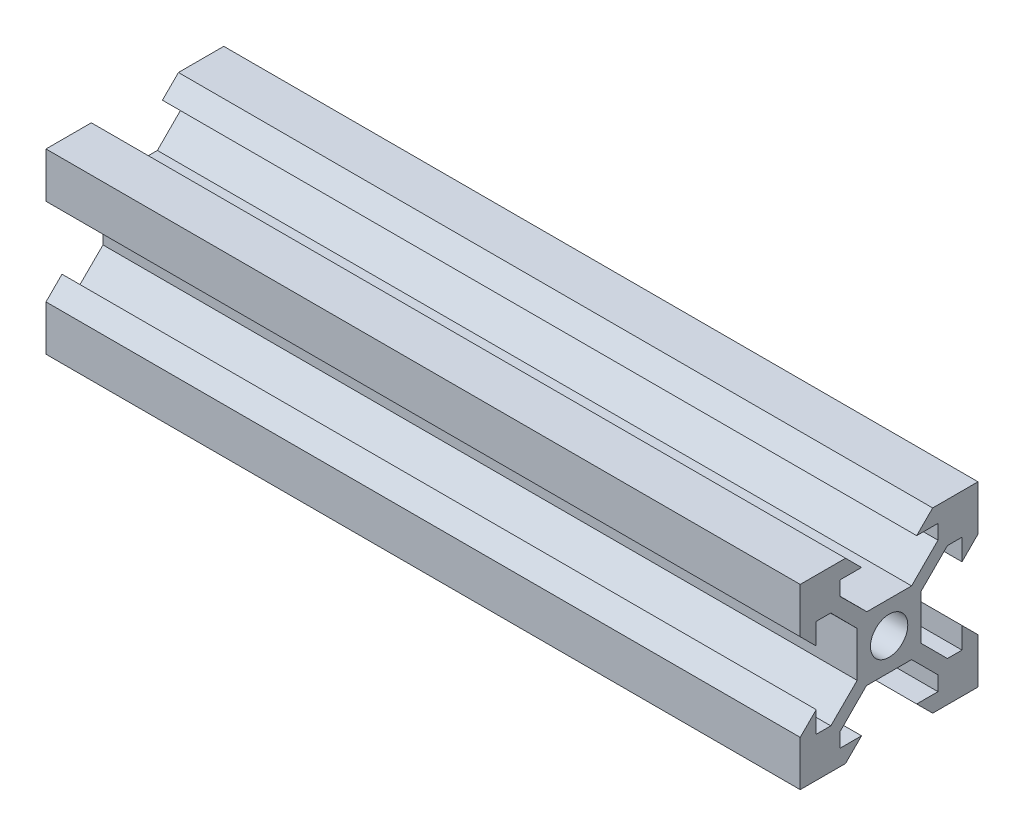
SolidWorks part; units mm, degrees
ref_plane "Front Plane" through (0, 0, 0) normal (0, 0, 1) x (1, 0, 0)
ref_plane "Top Plane" through (0, 0, 0) normal (0, 1, 0) x (1, 0, 0)
ref_plane "Right Plane" through (0, 0, 0) normal (1, 0, 0) x (0, 0, -1)
other "Graphic1"
sketch "Sketch1" plane through (0, 0, 0) normal (1, 0, 0) x (0, 0, -1)
  line L0 (-10, 20) -> (-4.9, 20)
  line L1 (-4.9, 20) -> (-3.1, 18.2)
  line L2 (-3.1, 18.2) -> (-5.4993, 18.2)
  line L3 (-5.4993, 18.2) -> (-5.4993, 16.56)
  line L4 (-5.4993, 16.56) -> (-2.5026, 13.59)
  line L5 (-2.5026, 13.59) -> (2.5293, 13.59)
  line L6 (2.5293, 13.59) -> (5.4993, 16.56)
  line L7 (5.4993, 16.56) -> (5.4993, 18.2)
  line L8 (5.4993, 18.2) -> (3.1, 18.2)
  line L9 (3.1, 18.2) -> (4.9, 20)
  line L10 (4.9, 20) -> (10, 20)
  line L11 (10, 20) -> (10, 14.9)
  line L12 (10, 14.9) -> (8.2, 13.1)
  line L13 (8.2, 13.1) -> (8.2, 15.4993)
  line L14 (8.2, 15.4993) -> (6.56, 15.4993)
  line L15 (6.56, 15.4993) -> (3.59, 12.5293)
  line L16 (3.59, 12.5293) -> (3.59, 7.4707)
  line L17 (3.59, 7.4707) -> (6.56, 4.5007)
  line L18 (6.56, 4.5007) -> (8.2, 4.5007)
  line L19 (8.2, 4.5007) -> (8.2, 6.9)
  line L20 (8.2, 6.9) -> (10, 5.1)
  line L21 (10, 5.1) -> (10, 0)
  line L22 (10, 0) -> (4.9, 0)
  line L23 (4.9, 0) -> (3.1, 1.8)
  line L24 (3.1, 1.8) -> (5.4993, 1.8)
  line L25 (5.4993, 1.8) -> (5.4993, 3.44)
  line L26 (5.4993, 3.44) -> (2.5293, 6.41)
  line L27 (2.5293, 6.41) -> (-2.5559, 6.41)
  line L28 (-2.5559, 6.41) -> (-5.4993, 3.44)
  line L29 (-5.4993, 3.44) -> (-5.4993, 1.8)
  line L30 (-5.4993, 1.8) -> (-3.1, 1.8)
  line L31 (-3.1, 1.8) -> (-4.9, 0)
  line L32 (-4.9, 0) -> (-10, 0)
  line L33 (-10, 0) -> (-10, 5.1)
  line L34 (-10, 5.1) -> (-8.2, 6.9)
  line L35 (-8.2, 6.9) -> (-8.2, 4.5007)
  line L36 (-8.2, 4.5007) -> (-6.56, 4.5007)
  line L37 (-6.56, 4.5007) -> (-3.59, 7.4441)
  line L38 (-3.59, 7.4441) -> (-3.59, 12.5026)
  line L39 (-3.59, 12.5026) -> (-6.56, 15.4993)
  line L40 (-6.56, 15.4993) -> (-8.2, 15.4993)
  line L41 (-8.2, 13.1) -> (-10, 14.9)
  line L42 (-10, 14.9) -> (-10, 20)
  line L43 (-8.2, 13.1) -> (-8.2, 15.4993)
extrude "Boss-Extrude1" add sketch "Sketch1" along normal blind 84.85
sketch "Sketch2" plane through (84.85, 0, 0) normal (1, 0, 0) x (0, 0, -1)
  line L0 (-2.5559, 6.41) -> (2.5293, 6.41) construction
  line L3 (-3.59, 12.5026) -> (-3.59, 7.4441) construction
  circle A0 centre (0.0001, 10) radius 2.1
  dimension "D1" = 4.2
  dimension "D2" = 3.59
  dimension "D3" = 3.5901
extrude "Cut-Extrude1" cut sketch "Sketch2" against normal through all
